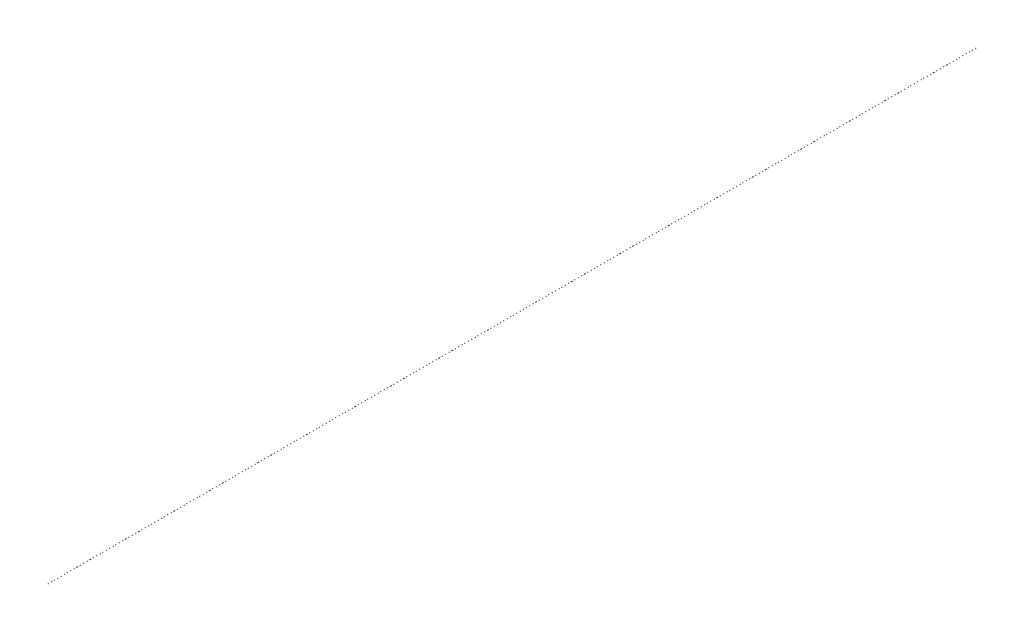
SolidWorks part; units mm, degrees
material "Balsa"
ref_plane "Front Plane" through (0, 0, 0) normal (0, 0, 1) x (1, 0, 0)
ref_plane "Top Plane" through (0, 0, 0) normal (0, 1, 0) x (1, 0, 0)
ref_plane "Right Plane" through (0, 0, 0) normal (1, 0, 0) x (0, 0, -1)
sketch "Sketch1" plane through (0, 0, 0) normal (0, 0, 1) x (1, 0, 0)
  line L0 (-0.1569, 0.0045) -> (-0.058, -0.065)
  line L1 (-0.1569, 0.0045) -> (-0.0909, 0.0986)
  line L2 (-0.058, -0.065) -> (0.0081, 0.0291)
  line L3 (-0.0909, 0.0986) -> (0.0081, 0.0291)
extrude "Boss-Extrude1" add sketch "Sketch1" against normal blind 1234.095
mirror "Mirror2" about plane through (0, 0, -1234.095) normal (0, 0, -1) of bodies 101
